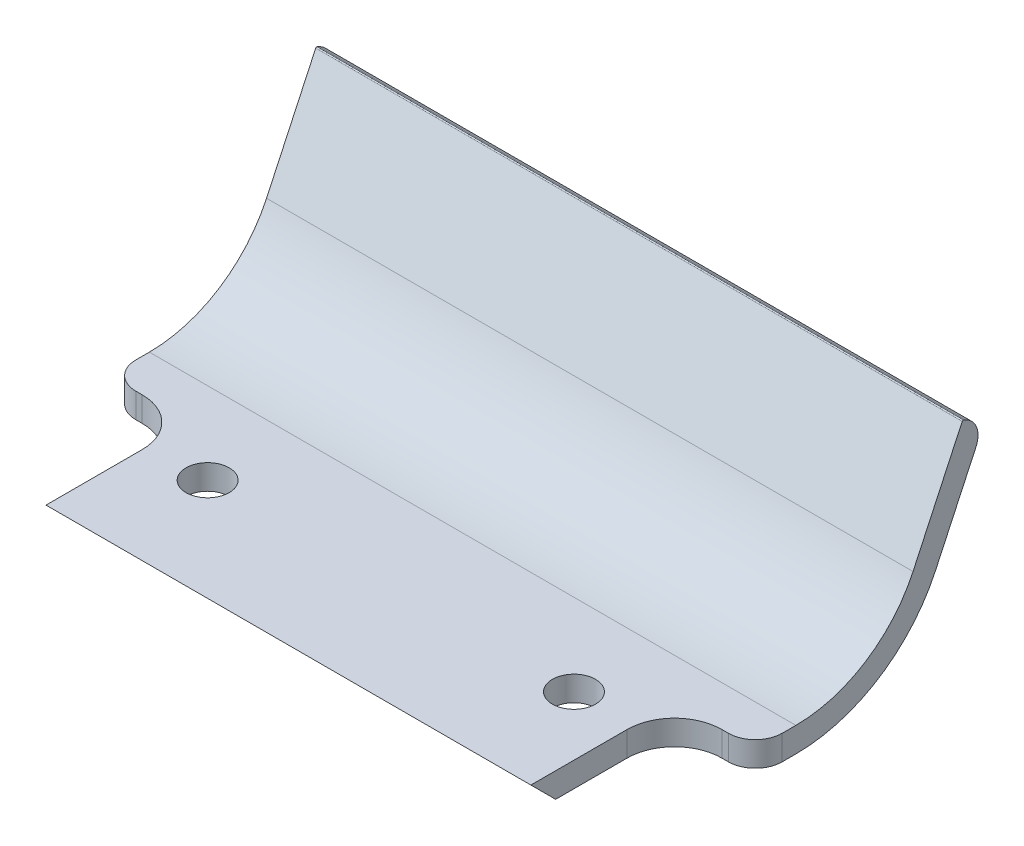
SolidWorks part; units mm, degrees
ref_plane "Front Plane" through (0, 0, 0) normal (0, 0, 1) x (1, 0, 0)
ref_plane "Top Plane" through (0, 0, 0) normal (0, 1, 0) x (1, 0, 0)
ref_plane "Right Plane" through (0, 0, 0) normal (1, 0, 0) x (0, 0, -1)
sketch "Sketch2" plane through (0, 0, 0) normal (1, 0, 0) x (0, 0, -1)
  line L0 (0, 0) -> (17.0932, 0)
  line L1 (27.9689, 6.9286) -> (32.5311, 16.7123)
  line L2 (24.738, 0) -> (24.738, 36.1592) construction
  line L3 (2.3, -2.3) -> (17.0932, -2.3)
  line L4 (30.0534, 5.9566) -> (33.8126, 14.0183)
  line L5 (0, 0) -> (2.3, -2.3)
  line L6 (0, -2.3) -> (17.0932, -2.3) construction
  line L7 (32.664, 16.7606) -> (32.8452, 16.6761)
  line L8 (30.0534, 5.9566) -> (34.6579, 15.8309) construction
  line L9 (27.9689, 6.9286) -> (32.5733, 16.8029) construction
  arc A0 (17.0932, 0) -> (27.9689, 6.9286) centre (17.0932, 12) ccw
  arc A1 (17.0932, -2.3) -> (30.0534, 5.9566) centre (17.0932, 12) ccw
  arc A2 (33.8126, 14.0183) -> (32.8452, 16.6761) centre (32, 14.8635) ccw
  arc A3 (32.5311, 16.7123) -> (32.664, 16.7606) centre (32.6217, 16.67) cw
  point P17 (34, 14.8635)
  point P21 (32.6217, 16.77)
  point P22 (0, 0)
  dimension "D2" = 12
  dimension "D6" = 2
  dimension "D7" = 0.1
  dimension "D1" = 25
  dimension "D3" = 34
  dimension "D5" = 45
  dimension "D8" = 19.07
  dimension "D4" = 2.3
extrude "Boss-Extrude1" add sketch "Sketch2" along normal mid plane 60
sketch "Sketch3" plane through (0, 0, 0) normal (0, 1, 0) x (1, 0, 0)
  line L0 (-30, 13.33) -> (-26.9, 13.33)
  line L1 (-22.5, 8.93) -> (-22.5, 0)
  line L2 (30, 0) -> (-30, 0) construction
  line L3 (0, -18.7) -> (0, 18.7) construction
  line L4 (-30, 17.0932) -> (-30, 0)
  line L5 (-30, 0) -> (30, 0)
  line L6 (30, 0) -> (30, 17.0932)
  line L7 (30, 17.0932) -> (-30, 17.0932)
  line L8 (-30, 17.0932) -> (-30, 0)
  line L9 (-30, 0) -> (30, 0)
  line L10 (30, 0) -> (30, 17.0932)
  line L11 (30, 17.0932) -> (-30, 17.0932)
  line L12 (22.5, 8.93) -> (22.5, 0)
  line L13 (30, 13.33) -> (26.9, 13.33)
  arc A0 (-26.9, 13.33) -> (-22.5, 8.93) centre (-26.9, 8.93) cw
  arc A1 (26.9, 13.33) -> (22.5, 8.93) centre (26.9, 8.93) ccw
  circle A2 centre (-17, 9.5) radius 2
  circle A3 centre (17, 9.5) radius 2
  line M8 (-30, 17.0932) -> (-30, 0)
  line M9 (-30, 0) -> (30, 0)
  line M10 (30, 0) -> (30, 17.0932)
  dimension "D4" = 4.4
  dimension "D7" = 4
  dimension "D2" = 22.5
  dimension "D3" = 13.33
  dimension "D5" = 34
  dimension "D6" = 9.5
  dimension "D1" = 0
extrude "Cut-Extrude1" cut sketch "Sketch3" against normal through all contours A0 L0 L1 M8 M9 | A2 | A3 | L13 A1 L12 L9 M10
fillet "Fillet1" radius 2.5 2 edges at (30, -1.15, -13.33) (-30, -1.15, -13.33)
